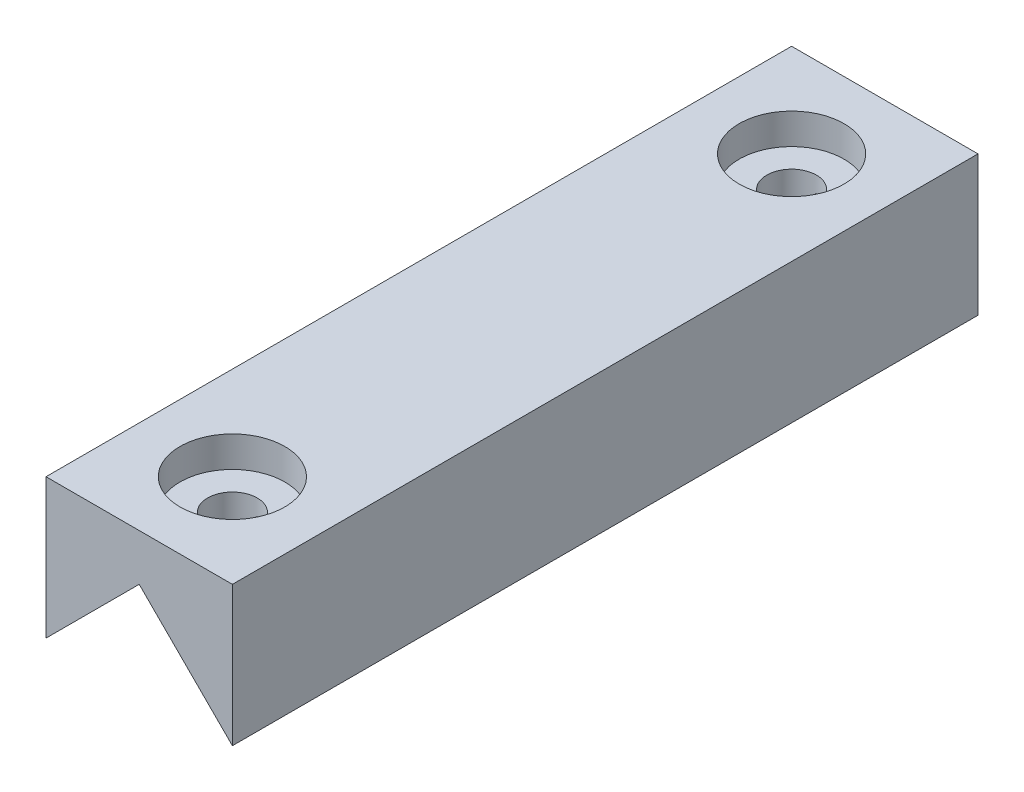
SolidWorks part; units mm, degrees
ref_plane "Front Plane" through (0, 0, 0) normal (0, 0, 1) x (1, 0, 0)
ref_plane "Top Plane" through (0, 0, 0) normal (0, 1, 0) x (1, 0, 0)
ref_plane "Right Plane" through (0, 0, 0) normal (1, 0, 0) x (0, 0, -1)
sketch "Sketch1" plane through (0, 0, 0) normal (0, 0, 1) x (1, 0, 0)
  line L0 (0, -19.05) -> (12.7, -6.35)
  line L1 (0, 0) -> (25.4, 0)
  line L2 (0, 0) -> (0, -19.05)
  line L4 (25.4, 0) -> (25.4, -19.05)
  line L5 (12.7, -6.35) -> (25.4, -19.05)
  dimension "D1" = 25.4
  dimension "D2" = 19.05
  dimension "D3" = 45
  dimension "D4" = 45
extrude "Boss-Extrude1" add sketch "Sketch1" along normal blind 101.6
hole_wizard "CBORE for 1/4 Binding Head Machine Screw1" positions "Sketch6" profile "Sketch7" counterbore size "1/4" standard "ANSI Inch" end condition through all
sketch "Sketch6" plane through (0, 0, 0) normal (0, 1, 0) x (1, 0, 0)
  line L0 (25.4, -101.6) -> (0, -101.6) construction
  line L1 (25.4, 0) -> (0, 0) construction
  line L2 (0, -101.6) -> (0, 0) construction
  point P0 (12.7, -88.9)
  point P2 (12.7, -12.7)
  dimension "D1" = 12.7
  dimension "D2" = 12.7
  dimension "D3" = 12.7
  dimension "D4" = 12.7
sketch "Sketch7" plane through (12.7, 0, 88.9) normal (1, 0, 0) x (0, 0, 1)
  line L0 (0, 0) -> (0, 19.05)
  line L1 (0, 19.05) -> (3.3782, 19.05)
  line L3 (3.3782, 19.05) -> (3.3782, 4.191)
  line L4 (3.3782, 4.191) -> (7.1437, 4.191)
  line L5 (7.1437, 4.191) -> (7.1437, 0)
  line L7 (7.1437, 0) -> (0, 0)
  line L11 (0, -6.35) -> (0, 107.95) construction
  dimension "Thru Hole Dia." = 6.7564
  dimension "Thru Hole Depth" = 19.05
  dimension "C'Bore Dia." = 14.2875
  dimension "C'Bore Depth" = 4.191
